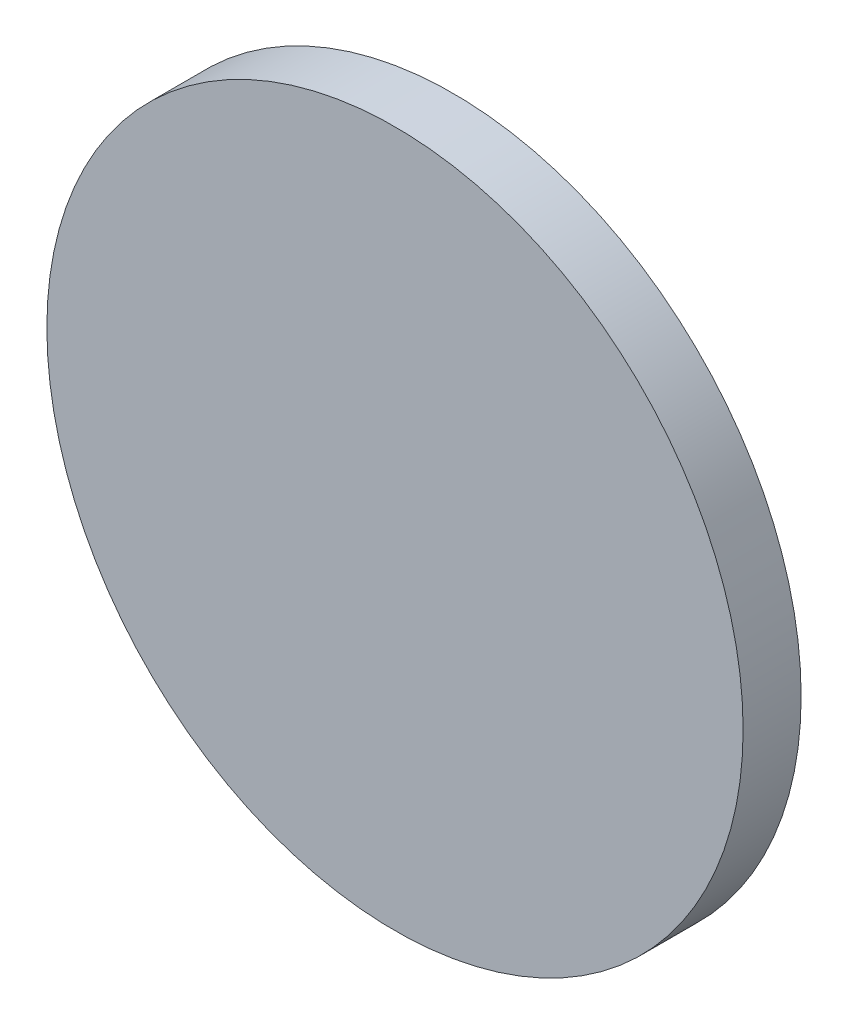
SolidWorks part; units mm, degrees
ref_plane "Front Plane" through (0, 0, 0) normal (0, 0, 1) x (1, 0, 0)
ref_plane "Top Plane" through (0, 0, 0) normal (0, 1, 0) x (1, 0, 0)
ref_plane "Right Plane" through (0, 0, 0) normal (1, 0, 0) x (0, 0, -1)
sketch "Sketch1" plane through (0, 0, 0) normal (0, 0, 1) x (1, 0, 0)
  circle A0 centre (0, 0) radius 60
  dimension "D1" = 120
extrude "Boss-Extrude1" add sketch "Sketch1" along normal blind 10
